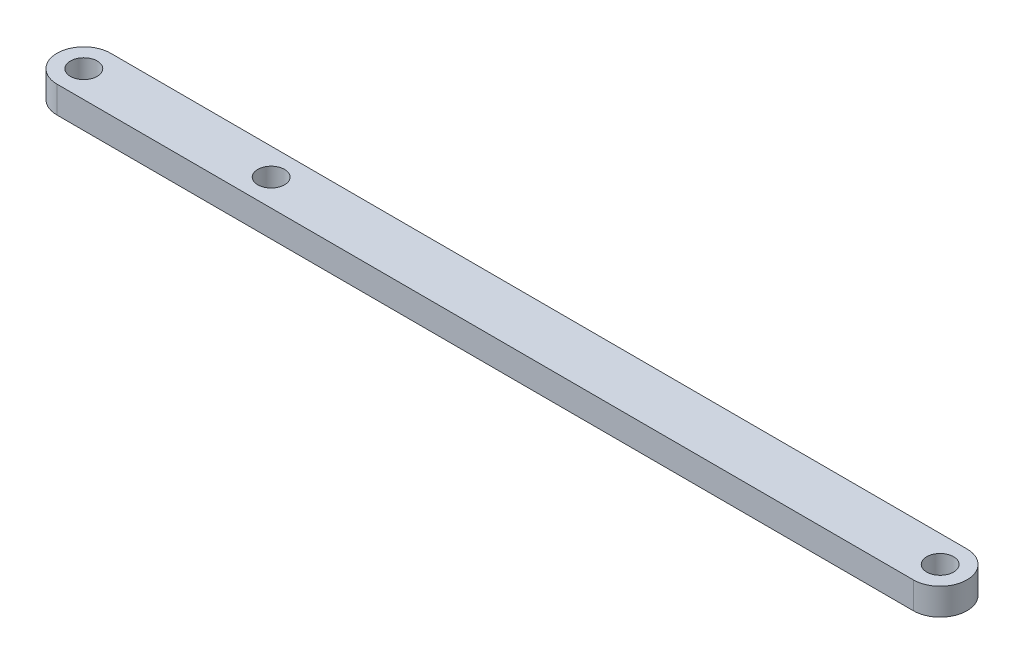
SolidWorks part; units mm, degrees
ref_plane "Front Plane" through (0, 0, 0) normal (0, 0, 1) x (1, 0, 0)
ref_plane "Top Plane" through (0, 0, 0) normal (0, 1, 0) x (1, 0, 0)
ref_plane "Right Plane" through (0, 0, 0) normal (1, 0, 0) x (0, 0, -1)
sketch "Sketch2" plane through (0, 0, 0) normal (0, 1, 0) x (1, 0, 0)
  line L0 (-80.6872, -3.3395) -> (79.3128, -3.5505) construction
  line L1 (-80.6806, 1.6605) -> (79.3194, 1.4495)
  line L2 (-80.6938, -8.3395) -> (79.3062, -8.5505)
  arc A0 (-80.6806, 1.6605) -> (-80.6938, -8.3395) centre (-80.6872, -3.3395) ccw
  arc A1 (79.3062, -8.5505) -> (79.3194, 1.4495) centre (79.3128, -3.5505) ccw
  point P2 (-0.6872, -3.445)
  dimension "D1" = 160
  dimension "D2" = 10
extrude "Boss-Extrude1" add sketch "Sketch2" along normal blind 5
sketch "Sketch3" plane through (0, 5, 0) normal (0, 1, 0) x (1, 0, 0)
  line L0 (79.3194, 1.4495) -> (-80.6806, 1.6605) construction
  circle A0 centre (-80.6872, -3.3395) radius 2.5
  circle A1 centre (79.3128, -3.5505) radius 2.5
  arc A2 (79.3062, -8.5505) -> (79.3194, 1.4495) centre (79.3128, -3.5505) ccw construction
  circle A3 centre (-45.6872, -3.3857) radius 2.5
  point P9 (84.3128, -3.5571)
  dimension "D1" = 5
  dimension "D2" = 5
  dimension "D7" = 5
  dimension "D3" = 160
  dimension "D4" = 5
  dimension "D5" = 5
  dimension "D6" = 5
  dimension "D8" = 35
  dimension "D9" = 5
extrude "Cut-Extrude1" cut sketch "Sketch3" against normal up to next
